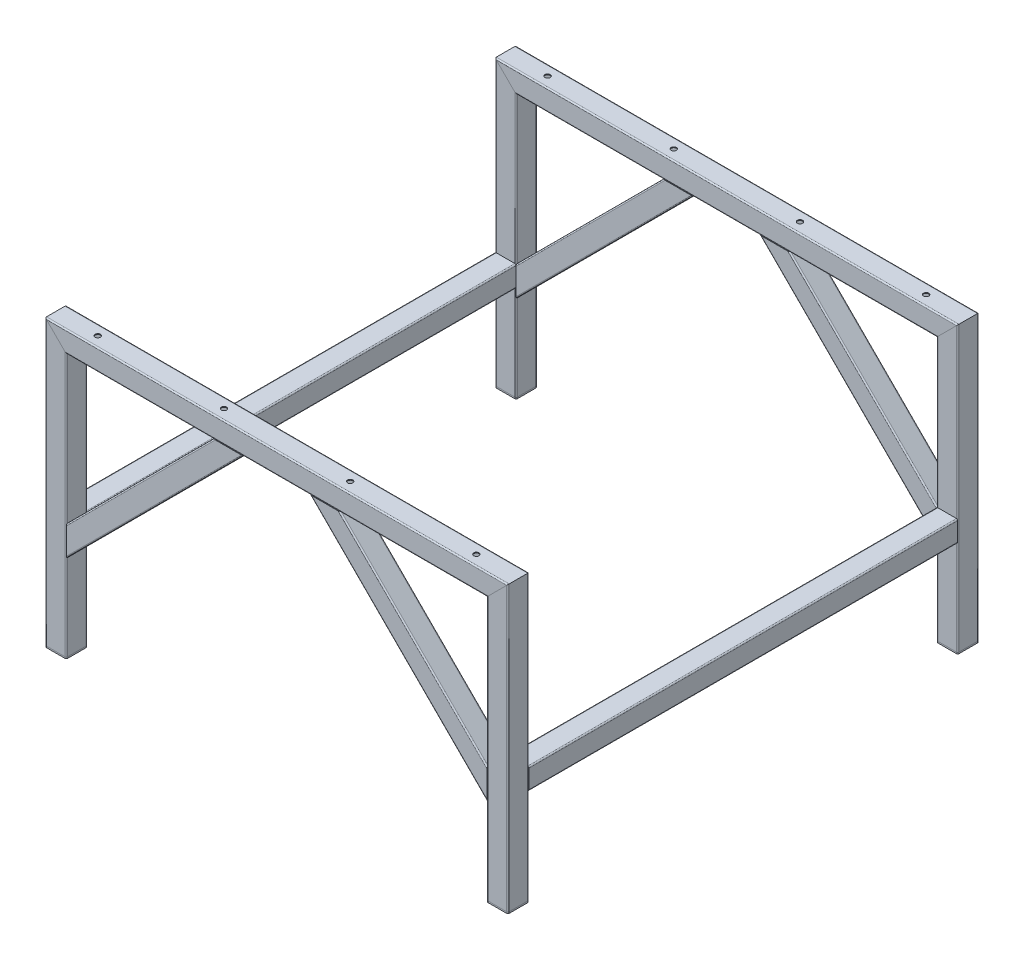
SolidWorks part; units mm, degrees
ref_plane "Plano frontal" through (0, 0, 0) normal (0, 0, 1) x (1, 0, 0)
ref_plane "Plano superior" through (0, 0, 0) normal (0, 1, 0) x (1, 0, 0)
ref_plane "Plano direito" through (0, 0, 0) normal (1, 0, 0) x (0, 0, -1)
sketch "Esboço1" plane through (0, 0, 0) normal (0, 1, 0) x (1, 0, 0)
  line L1 (-533.4, 543.25) -> (533.4, 543.25) construction
  line L2 (-533.4, 543.25) -> (-533.4, -543.25) construction
  line L3 (-533.4, -543.25) -> (533.4, -543.25) construction
  line L4 (533.4, 543.25) -> (533.4, -543.25) construction
  line L5 (-533.4, 543.25) -> (533.4, -543.25) construction
  line L6 (-533.4, -543.25) -> (533.4, 543.25) construction
  point P0 (0, 0)
  dimension "D1" = 1086.5
  dimension "D2" = 1066.8
ref_plane "Plano10" through (0, 218.08, 0) normal (0, 1, 0) x (1, 0, 0)
sketch "Esboço12" plane through (0, 218.08, 0) normal (0, 1, 0) x (1, 0, 0)
  line L1 (-533.4, -543.25) -> (533.4, -543.25)
  line L2 (-533.4, -543.25) -> (-533.4, 543.25)
  line L3 (-533.4, 543.25) -> (533.4, 543.25)
  line L4 (533.4, -543.25) -> (533.4, 543.25)
  line L5 (-533.4, -543.25) -> (533.4, 543.25) construction
  line L6 (-533.4, 543.25) -> (533.4, -543.25) construction
  point P0 (0, 0)
ref_plane "Plano1" through (0, 660.4, 0) normal (0, 1, 0) x (1, 0, 0)
sketch "Esboço2" plane through (0, 660.4, 0) normal (0, 1, 0) x (1, 0, 0)
  line L0 (-533.4, -543.25) -> (533.4, -543.25) construction
  line L1 (533.4, 543.25) -> (533.4, -543.25) construction
  line L2 (-533.4, 543.25) -> (-533.4, -543.25) construction
  line L3 (-533.4, 543.25) -> (533.4, 543.25) construction
  line L4 (-533.4, -543.25) -> (533.4, -543.25) construction
  line L5 (533.4, 543.25) -> (533.4, -543.25) construction
  line L6 (-533.4, 543.25) -> (-533.4, -543.25) construction
  line L7 (-533.4, 543.25) -> (533.4, 543.25) construction
ref_plane "Plano2" through (0, 254, 0) normal (0, 1, 0) x (1, 0, 0)
sketch "Esboço4" plane through (0, 254, 0) normal (0, 1, 0) x (1, 0, 0)
  line L0 (-533.4, -543.25) -> (533.4, -543.25) construction
  line L1 (533.4, 543.25) -> (533.4, -543.25) construction
  line L2 (-533.4, 543.25) -> (533.4, 543.25) construction
  line L3 (-533.4, 543.25) -> (-533.4, -543.25) construction
  line L4 (-533.4, -543.25) -> (533.4, -543.25) construction
  line L5 (533.4, 543.25) -> (533.4, -543.25) construction
  line L6 (-533.4, 543.25) -> (533.4, 543.25) construction
  line L7 (-533.4, 543.25) -> (-533.4, -543.25) construction
sketch3d "3DSketch2"
  line L0 (533.4, 660.4, 543.25) -> (533.4, 0, 543.25)
  line L1 (533.4, 660.4, -543.25) -> (533.4, 0, -543.25)
  line L2 (-533.4, 660.4, 543.25) -> (-533.4, 0, 543.25)
  line L3 (-533.4, 660.4, -543.25) -> (-533.4, 0, -543.25)
  line L4 (-533.4, 660.4, 543.25) -> (533.4, 660.4, 543.25)
  line L5 (-533.4, 660.4, -543.25) -> (533.4, 660.4, -543.25)
  line L6 (533.4, 254, -543.25) -> (533.4, 254, 543.25)
  line L7 (-533.4, 254, 543.25) -> (-533.4, 254, -543.25)
  line L8 (91.08, 660.4, -543.25) -> (533.4, 218.08, -543.25)
  line L11 (91.08, 660.4, 543.25) -> (533.4, 218.08, 543.25)
  line L12 (-91.08, 660.4, 543.25) -> (-533.4, 218.08, 543.25)
  line L13 (-533.4, 218.08, -543.25) -> (-91.08, 660.4, -543.25)
  dimension "D1" = 45
  dimension "D3" = 45
  dimension "D2" = 45
  dimension "D4" = 45
other "Metalon quadrado TUBO2POLX2POLX2(1)"
ref_plane "Plano3" through (-533.4, 660.4, 543.25) normal (0, -1, 0) x (1, 0, 0)
sketch "Sketch2" plane through (-533.4, 660.4, 543.25) normal (0, -1, 0) x (1, 0, 0)
  line L0 (-22.4, 23.4) -> (22.4, 23.4)
  line L1 (-22.4, -25.4) -> (22.4, -25.4)
  line L2 (-25.4, -22.4) -> (-25.4, 22.4)
  line L3 (-22.4, 25.4) -> (22.4, 25.4)
  line L4 (25.4, -22.4) -> (25.4, 22.4)
  line L5 (-25.4, -25.4) -> (25.4, 25.4) construction
  line L6 (-25.4, 25.4) -> (25.4, -25.4) construction
  line L7 (23.4, -22.4) -> (23.4, 22.4)
  line L8 (-22.4, -23.4) -> (22.4, -23.4)
  line L9 (-23.4, -22.4) -> (-23.4, 22.4)
  arc A0 (22.4, 25.4) -> (25.4, 22.4) centre (22.4, 22.4) cw
  arc A1 (25.4, -22.4) -> (22.4, -25.4) centre (22.4, -22.4) cw
  arc A2 (-22.4, -25.4) -> (-25.4, -22.4) centre (-22.4, -22.4) cw
  arc A3 (-25.4, 22.4) -> (-22.4, 25.4) centre (-22.4, 22.4) cw
  arc A4 (22.4, 23.4) -> (23.4, 22.4) centre (22.4, 22.4) cw
  arc A5 (23.4, -22.4) -> (22.4, -23.4) centre (22.4, -22.4) cw
  arc A6 (-22.4, -23.4) -> (-23.4, -22.4) centre (-22.4, -22.4) cw
  arc A7 (-23.4, 22.4) -> (-22.4, 23.4) centre (-22.4, 22.4) cw
  point P0 (0, 0)
  point P30 (0, 0)
  dimension "D3" = 3
  dimension "D1" = 50.8
  dimension "D2" = 50.8
  dimension "D4" = 2
other "Metalon quadrado TUBO2POLX2POLX2(2)"
ref_plane "Plano4" through (533.4, 660.4, -543.25) normal (0, -1, 0) x (1, 0, 0)
sketch "Sketch21" plane through (533.4, 660.4, -543.25) normal (0, -1, 0) x (1, 0, 0)
  line L0 (-22.4, 23.4) -> (22.4, 23.4)
  line L1 (-22.4, -25.4) -> (22.4, -25.4)
  line L2 (-25.4, -22.4) -> (-25.4, 22.4)
  line L3 (-22.4, 25.4) -> (22.4, 25.4)
  line L4 (25.4, -22.4) -> (25.4, 22.4)
  line L5 (-25.4, -25.4) -> (25.4, 25.4) construction
  line L6 (-25.4, 25.4) -> (25.4, -25.4) construction
  line L7 (23.4, -22.4) -> (23.4, 22.4)
  line L8 (-22.4, -23.4) -> (22.4, -23.4)
  line L9 (-23.4, -22.4) -> (-23.4, 22.4)
  arc A0 (22.4, 25.4) -> (25.4, 22.4) centre (22.4, 22.4) cw
  arc A1 (25.4, -22.4) -> (22.4, -25.4) centre (22.4, -22.4) cw
  arc A2 (-22.4, -25.4) -> (-25.4, -22.4) centre (-22.4, -22.4) cw
  arc A3 (-25.4, 22.4) -> (-22.4, 25.4) centre (-22.4, 22.4) cw
  arc A4 (22.4, 23.4) -> (23.4, 22.4) centre (22.4, 22.4) cw
  arc A5 (23.4, -22.4) -> (22.4, -23.4) centre (22.4, -22.4) cw
  arc A6 (-22.4, -23.4) -> (-23.4, -22.4) centre (-22.4, -22.4) cw
  arc A7 (-23.4, 22.4) -> (-22.4, 23.4) centre (-22.4, 22.4) cw
  point P0 (0, 0)
  point P30 (0, 0)
  dimension "D3" = 3
  dimension "D1" = 50.8
  dimension "D2" = 50.8
  dimension "D4" = 2
other "Metalon quadrado TUBO2POLX2POLX2(3)"
ref_plane "Plano7" through (533.4, 254, -543.25) normal (0, 0, 1) x (1, 0, 0)
sketch "Sketch24" plane through (533.4, 254, -543.25) normal (0, 0, 1) x (1, 0, 0)
  line L0 (-22.4, 23.4) -> (22.4, 23.4)
  line L1 (-22.4, -25.4) -> (22.4, -25.4)
  line L2 (-25.4, -22.4) -> (-25.4, 22.4)
  line L3 (-22.4, 25.4) -> (22.4, 25.4)
  line L4 (25.4, -22.4) -> (25.4, 22.4)
  line L5 (-25.4, -25.4) -> (25.4, 25.4) construction
  line L6 (-25.4, 25.4) -> (25.4, -25.4) construction
  line L7 (23.4, -22.4) -> (23.4, 22.4)
  line L8 (-22.4, -23.4) -> (22.4, -23.4)
  line L9 (-23.4, -22.4) -> (-23.4, 22.4)
  arc A0 (22.4, 25.4) -> (25.4, 22.4) centre (22.4, 22.4) cw
  arc A1 (25.4, -22.4) -> (22.4, -25.4) centre (22.4, -22.4) cw
  arc A2 (-22.4, -25.4) -> (-25.4, -22.4) centre (-22.4, -22.4) cw
  arc A3 (-25.4, 22.4) -> (-22.4, 25.4) centre (-22.4, 22.4) cw
  arc A4 (22.4, 23.4) -> (23.4, 22.4) centre (22.4, 22.4) cw
  arc A5 (23.4, -22.4) -> (22.4, -23.4) centre (22.4, -22.4) cw
  arc A6 (-22.4, -23.4) -> (-23.4, -22.4) centre (-22.4, -22.4) cw
  arc A7 (-23.4, 22.4) -> (-22.4, 23.4) centre (-22.4, 22.4) cw
  point P0 (0, 0)
  point P30 (0, 0)
  dimension "D3" = 3
  dimension "D1" = 50.8
  dimension "D2" = 50.8
  dimension "D4" = 2
other "Aparar/Estender5"
other "Aparar/Estender6"
other "Metalon quadrado TUBO2POLX2POLX2(8)"
ref_plane "Plano11" through (91.08, 660.4, -543.25) normal (0.7071, -0.7071, 0) x (0.7071, 0.7071, 0)
sketch "Sketch27" plane through (91.08, 660.4, -543.25) normal (0.7071, -0.7071, 0) x (0.7071, 0.7071, 0)
  line L0 (-22.4, 23.4) -> (22.4, 23.4)
  line L1 (-22.4, -25.4) -> (22.4, -25.4)
  line L2 (-25.4, -22.4) -> (-25.4, 22.4)
  line L3 (-22.4, 25.4) -> (22.4, 25.4)
  line L4 (25.4, -22.4) -> (25.4, 22.4)
  line L5 (-25.4, -25.4) -> (25.4, 25.4) construction
  line L6 (-25.4, 25.4) -> (25.4, -25.4) construction
  line L7 (23.4, -22.4) -> (23.4, 22.4)
  line L8 (-22.4, -23.4) -> (22.4, -23.4)
  line L9 (-23.4, -22.4) -> (-23.4, 22.4)
  arc A0 (22.4, 25.4) -> (25.4, 22.4) centre (22.4, 22.4) cw
  arc A1 (25.4, -22.4) -> (22.4, -25.4) centre (22.4, -22.4) cw
  arc A2 (-22.4, -25.4) -> (-25.4, -22.4) centre (-22.4, -22.4) cw
  arc A3 (-25.4, 22.4) -> (-22.4, 25.4) centre (-22.4, 22.4) cw
  arc A4 (22.4, 23.4) -> (23.4, 22.4) centre (22.4, 22.4) cw
  arc A5 (23.4, -22.4) -> (22.4, -23.4) centre (22.4, -22.4) cw
  arc A6 (-22.4, -23.4) -> (-23.4, -22.4) centre (-22.4, -22.4) cw
  arc A7 (-23.4, 22.4) -> (-22.4, 23.4) centre (-22.4, 22.4) cw
  point P0 (0, 0)
  point P30 (0, 0)
  dimension "D3" = 3
  dimension "D1" = 50.8
  dimension "D2" = 50.8
  dimension "D4" = 2
other "Metalon quadrado TUBO2POLX2POLX2(9)"
ref_plane "Plano12" through (-91.08, 660.4, 543.25) normal (-0.7071, -0.7071, 0) x (0, 0, 1)
sketch "Sketch28" plane through (-91.08, 660.4, 543.25) normal (-0.7071, -0.7071, 0) x (0, 0, 1)
  line L0 (-22.4, 23.4) -> (22.4, 23.4)
  line L1 (-22.4, -25.4) -> (22.4, -25.4)
  line L2 (-25.4, -22.4) -> (-25.4, 22.4)
  line L3 (-22.4, 25.4) -> (22.4, 25.4)
  line L4 (25.4, -22.4) -> (25.4, 22.4)
  line L5 (-25.4, -25.4) -> (25.4, 25.4) construction
  line L6 (-25.4, 25.4) -> (25.4, -25.4) construction
  line L7 (23.4, -22.4) -> (23.4, 22.4)
  line L8 (-22.4, -23.4) -> (22.4, -23.4)
  line L9 (-23.4, -22.4) -> (-23.4, 22.4)
  arc A0 (22.4, 25.4) -> (25.4, 22.4) centre (22.4, 22.4) cw
  arc A1 (25.4, -22.4) -> (22.4, -25.4) centre (22.4, -22.4) cw
  arc A2 (-22.4, -25.4) -> (-25.4, -22.4) centre (-22.4, -22.4) cw
  arc A3 (-25.4, 22.4) -> (-22.4, 25.4) centre (-22.4, 22.4) cw
  arc A4 (22.4, 23.4) -> (23.4, 22.4) centre (22.4, 22.4) cw
  arc A5 (23.4, -22.4) -> (22.4, -23.4) centre (22.4, -22.4) cw
  arc A6 (-22.4, -23.4) -> (-23.4, -22.4) centre (-22.4, -22.4) cw
  arc A7 (-23.4, 22.4) -> (-22.4, 23.4) centre (-22.4, 22.4) cw
  point P0 (0, 0)
  point P30 (0, 0)
  dimension "D3" = 3
  dimension "D1" = 50.8
  dimension "D2" = 50.8
  dimension "D4" = 2
other "Aparar/Estender7"
other "Aparar/Estender8"
other "Aparar/Estender9"
other "Aparar/Estender10"
sketch "Esboço15" plane through (0, 685.8, 0) normal (0, 1, 0) x (1, 0, 0)
  line L0 (-558.8, -543.25) -> (558.8, -543.25) construction
  line L1 (-558.8, -565.65) -> (-558.8, -520.85) construction
  line L2 (558.8, -565.65) -> (558.8, -520.85) construction
  line L3 (558.8, -520.85) -> (558.8, -565.65) construction
  line L4 (0, 0) -> (-1003.6023, 0) construction
  line L5 (0, 0) -> (0, 754.3173) construction
  line L6 (-558.8, 543.25) -> (558.8, 543.25) construction
  circle A0 centre (457.2, -543.25) radius 6.35
  circle A1 centre (152.4, -543.25) radius 6.35
  circle A2 centre (-152.4, -543.25) radius 6.35
  circle A3 centre (-457.2, -543.25) radius 6.35
  circle A4 centre (-457.2, 543.25) radius 6.35
  circle A5 centre (-152.4, 543.25) radius 6.35
  circle A6 centre (152.4, 543.25) radius 6.35
  circle A7 centre (457.2, 543.25) radius 6.35
  dimension "D1" = 12.7
  dimension "D2" = 101.6
  dimension "D3" = 12.7
  dimension "D4" = 304.8
  dimension "D5" = 12.7
  dimension "D6" = 304.8
  dimension "D7" = 12.7
  dimension "D8" = 304.8
extrude "Corte-extrusão2" cut sketch "Esboço15" against normal blind 10
sketch "Esboço17" plane through (0, 0, 0) normal (0, -1, 0) x (1, 0, 0)
  line L0 (508, 520.85) -> (508, 565.65) construction
  line L1 (555.8, 517.85) -> (511, 517.85) construction
  line L2 (558.8, 565.65) -> (558.8, 520.85) construction
  line L3 (511, 568.65) -> (555.8, 568.65) construction
  line L4 (508, 520.85) -> (508, 565.65)
  line L5 (555.8, 517.85) -> (511, 517.85)
  line L6 (558.8, 565.65) -> (558.8, 520.85)
  line L7 (511, 568.65) -> (555.8, 568.65)
  line L8 (0, 0) -> (0, 1010.7332) construction
  line L9 (0, 0) -> (1081.4183, 0) construction
  line L10 (511, -568.65) -> (555.8, -568.65)
  line L11 (558.8, -565.65) -> (558.8, -520.85)
  line L12 (555.8, -517.85) -> (511, -517.85)
  line L13 (508, -520.85) -> (508, -565.65)
  line L14 (-508, -520.85) -> (-508, -565.65)
  line L15 (-555.8, -517.85) -> (-511, -517.85)
  line L16 (-558.8, -565.65) -> (-558.8, -520.85)
  line L17 (-511, -568.65) -> (-555.8, -568.65)
  line L18 (-511, 568.65) -> (-555.8, 568.65)
  line L19 (-558.8, 565.65) -> (-558.8, 520.85)
  line L20 (-555.8, 517.85) -> (-511, 517.85)
  line L21 (-508, 520.85) -> (-508, 565.65)
  arc A0 (508, 520.85) -> (511, 517.85) centre (511, 520.85) ccw construction
  arc A1 (555.8, 517.85) -> (558.8, 520.85) centre (555.8, 520.85) ccw construction
  arc A2 (558.8, 565.65) -> (555.8, 568.65) centre (555.8, 565.65) ccw construction
  arc A3 (511, 568.65) -> (508, 565.65) centre (511, 565.65) ccw construction
  arc A4 (508, 520.85) -> (511, 517.85) centre (511, 520.85) ccw
  arc A5 (555.8, 517.85) -> (558.8, 520.85) centre (555.8, 520.85) ccw
  arc A6 (558.8, 565.65) -> (555.8, 568.65) centre (555.8, 565.65) ccw
  arc A7 (511, 568.65) -> (508, 565.65) centre (511, 565.65) ccw
  arc A8 (511, -568.65) -> (508, -565.65) centre (511, -565.65) cw
  arc A9 (558.8, -565.65) -> (555.8, -568.65) centre (555.8, -565.65) cw
  arc A10 (555.8, -517.85) -> (558.8, -520.85) centre (555.8, -520.85) cw
  arc A11 (508, -520.85) -> (511, -517.85) centre (511, -520.85) cw
  arc A12 (-508, -520.85) -> (-511, -517.85) centre (-511, -520.85) ccw
  arc A13 (-555.8, -517.85) -> (-558.8, -520.85) centre (-555.8, -520.85) ccw
  arc A14 (-558.8, -565.65) -> (-555.8, -568.65) centre (-555.8, -565.65) ccw
  arc A15 (-511, -568.65) -> (-508, -565.65) centre (-511, -565.65) ccw
  arc A16 (-511, 568.65) -> (-508, 565.65) centre (-511, 565.65) cw
  arc A17 (-558.8, 565.65) -> (-555.8, 568.65) centre (-555.8, 565.65) cw
  arc A18 (-555.8, 517.85) -> (-558.8, 520.85) centre (-555.8, 520.85) cw
  arc A19 (-508, 520.85) -> (-511, 517.85) centre (-511, 520.85) cw
extrude "Ressalto-extrusão1" add sketch "Esboço17" along normal blind 3.5 separate body
equation "\"D1@Sketch2\"=\"D2@Sketch2\""
equation "\"D1@Sketch21\"=\"D2@Sketch21\""
equation "\"D1@Sketch24\"=\"D2@Sketch24\""
equation "\"D1@Sketch25\"=\"D2@Sketch25\""
equation "\"D1@Sketch26\"=\"D2@Sketch26\""
equation "\"D1@Sketch27\"=\"D2@Sketch27\""
equation "\"D1@Sketch28\"=\"D2@Sketch28\""
